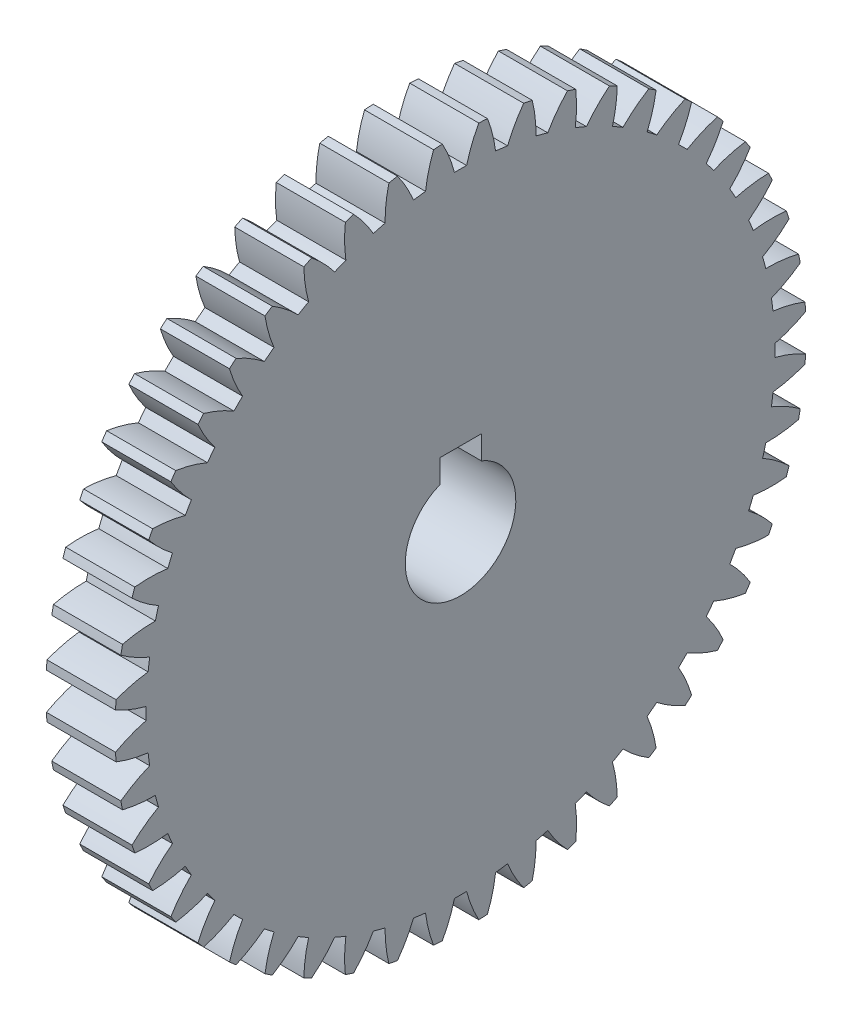
SolidWorks part; units mm, degrees
ref_plane "Plane1" through (0, 0, 0) normal (0, 0, 1) x (1, 0, 0)
ref_plane "Plane2" through (0, 0, 0) normal (0, 1, 0) x (1, 0, 0)
ref_plane "Plane3" through (0, 0, 0) normal (1, 0, 0) x (0, 0, -1)
other "Configuration Table"
sketch "HoldingSke" plane through (0, 0, 0) normal (0, 1, 0) x (1, 0, 0)
  line L0 (0, 0) -> (0.6691, -0.7431)
  line L1 (-15, 0) -> (100, 0) construction
  line L2 (0, 0) -> (-2.1039, 2.3779)
  line L3 (0, 0) -> (-11.863, 4.5341)
  line L4 (0, 0) -> (5.7786, 6.4178)
  line L5 (0, 0) -> (-9.3695, -3.4946)
  line L6 (0, 0) -> (-4.1448, -2.7965)
  line L7 (-2.1039, 2.3779) -> (0.0486, 12.1435)
  line L8 (-76.2, 54.61) -> (-74.8, 54.61)
  line L9 (-71.009, 38.7566) -> (-53.1078, 45.2721)
  line L10 (-76.2, 71.12) -> (104.1128, 71.12)
  line L11 (0, 0) -> (-5, 0)
  line L12 (-76.2, 101.6) -> (-76.162, 101.6)
  line L13 (24.9733, 27.94) -> (52.9518, 28.4284)
  line L14 (24.9733, 27.94) -> (24.9743, 27.94)
  line L15 (24.9733, 27.94) -> (100.4006, 29.5858)
  line L16 (-63.627, -1) -> (-12.827, -1)
  circle A0 centre (0, 0) radius 4
  circle A1 centre (0, 0) radius 5
  circle A2 centre (0, 0) radius 5
  circle A3 centre (0, 0) radius 4
  dimension "MHD" = 10
  dimension "Hub_dia" = 10
  dimension "Bore" = 8
  dimension "MBD" = 8
  dimension "Num_teeth" = 48
  dimension "Pitch" = 1
  dimension "Overall_len" = 10
  dimension "Show_teeth" = 48
  dimension "Thickness" = 5
  dimension "OAL" = 10.0001
  dimension "T_dim" = 1.4
  dimension "Ap" = 20
  dimension "H" = 19.05
  dimension "Pitch_radius" = 180.3128
  dimension "Width" = 5
  dimension "Backlash" = 0.038
  dimension "Addendum_fac" = 1
  dimension "Dedendum_fac" = 1.25
  dimension "Clearance_fac" = 0.25
  dimension "Dedendum_add" = 0.001
  dimension "Module" = 1
sketch "BasProSke" plane through (0, 0, 0) normal (0, 1, 0) x (1, 0, 0)
  line L0 (-10, 0) -> (60, 0) construction
  line L1 (0, 0) -> (0, 25)
  line L2 (0, 0) -> (5, 0)
  line L3 (5, 0) -> (5, 25)
  line L4 (5, 25) -> (0, 25)
  dimension "Thickness" = 5
  dimension "Diameter" = 50
revolve "Base-Revolve" add sketch "BasProSke" angle 360 about L0
sketch "TooCutSke" plane through (0, 0, 0) normal (1, 0, 0) x (0, 0, -1)
  line L1 (0, 0) -> (0, 107) construction
  line L2 (0, 0) -> (-0.8518, 23.9849) construction
  line L3 (0, 0) -> (-3.1379, 47.8757) construction
  line L4 (-0.8518, 23.9849) -> (-1.569, 23.9379) construction
  arc A0 (0.4395, 22.7448) -> (-0.4395, 22.7448) centre (0, 0) ccw
  arc A1 (1.3336, 24.9898) -> (-1.3336, 24.9898) centre (0, 0) ccw
  circle A2 centre (0, 0) radius 24 construction
  circle A3 centre (0, 0) radius 22.5526 construction
  arc A4 (-0.4395, 22.7448) -> (-1.3336, 24.9898) centre (-9.7344, 20.3436) ccw
  arc A5 (1.3336, 24.9898) -> (0.4395, 22.7448) centre (9.7344, 20.3436) ccw
  dimension "Root_dia" = 45.498
  dimension "Overcut_dia" = 50.0508
  dimension "Pitch_dia" = 48
  dimension "Base_dia" = 45.1052
  dimension "Flank_rad" = 9.6
  dimension "Half_ang" = 3.75
  dimension "Half_CT" = 0.7188
extrude "ToothCut" cut sketch "TooCutSke" along normal through all
fillet "Breaks" [suppressed] radius 0.02
fillet "RootFillets" [suppressed] radius 0.251
pattern_circular "TeethCuts" count 48 every 7.5 about axis through (-10, 0, 0) along (1, 0, 0) of "ToothCut", "RootFillets", "Breaks"
sketch "HubNeaOneSke" plane through (0, 0, 0) normal (-1, 0, 0) x (0, 0, 1)
  circle A0 centre (0, 0) radius 5
  dimension "Diameter" = 10
extrude "HubNearOne" add sketch "HubNeaOneSke" along normal blind 5.0001
sketch "HubNeaBotSke" plane through (0, 0, 0) normal (-1, 0, 0) x (0, 0, 1)
  circle A0 centre (0, 0) radius 5
  dimension "Diameter" = 10
extrude "HubNearBoth" [suppressed] add sketch "HubNeaBotSke" along normal blind 2.5
ref_plane "FarPln" through (5, 0, 0) normal (1, 0, 0) x (0, 0, -1)
sketch "HubFarSke" plane through (5, 0, 0) normal (1, 0, 0) x (0, 0, -1)
  circle A0 centre (0, 0) radius 5
  dimension "Diameter" = 10
extrude "HubFar" [suppressed] add sketch "HubFarSke" along normal blind 2.5
sketch "BorSke" plane through (0, 0, 0) normal (1, 0, 0) x (0, 0, -1)
  circle A0 centre (0, 0) radius 4
  dimension "Diameter" = 8
extrude "Bore" cut sketch "BorSke" along normal mid plane 20.0001
sketch "KeySke" plane through (0, 0, 0) normal (1, 0, 0) x (0, 0, -1)
  line L0 (-1.5, 0) -> (-1.5, 5.4)
  line L1 (-1.5, 5.4) -> (1.5, 5.4)
  line L2 (1.5, 5.4) -> (1.5, 0)
  line L3 (0, 0) -> (0, 34) construction
  line L4 (-1.5, 0) -> (1.5, 0)
  dimension "Offset" = 5.4
  dimension "Width" = 3
extrude "Keyway" cut sketch "KeySke" along normal mid plane 20.0001
pattern_circular "Keyway2" [suppressed] count 2 every 90 about axis through (-10, 0, 0) along (1, 0, 0)
equation "' \"Module@HoldingSke\" = 6.35"
equation "' \"Num_teeth@HoldingSke\" = 12"
equation "' \"Ap@HoldingSke\" =  20"
equation "' \"Ap@HoldingSke\" = 20"
equation "' \"Width@HoldingSke\" = 0.5 * 25.4"
equation "' \"Hub_dia@HoldingSke\"= 1 * 25.4"
equation "' \"Hub_dia@HoldingSke\" = 1 * 25.4"
equation "' \"Overall_len@HoldingSke\" = 1.0 * 25.4"
equation "' \"Bore@HoldingSke\" = 0.75 * 25.4"
equation "' \"T_dim@HoldingSke\" = 0.1 * 25.4"
equation "' \"Width@KeySke\" = 0.25 * 25.4"
equation "' \"Show_teeth@HoldingSke\" = 13"
equation "' \"Backlash@HoldingSke\" = 0.009 * 25.4"
equation "' \"Addendum_fac@HoldingSke\" = 1.0"
equation "' \"Dedendum_fac@HoldingSke\" = 1.25"
equation "' \"Dedendum_add@HoldingSke\" = 0.00005 * 25.4"
equation "' \"Clearance_fac@HoldingSke\" = 0.25"
equation "\"Pitch@HoldingSke\" = 1 / \"Module@HoldingSke\""
equation "\"Overcut_dia@TooCutSke\" = (\"Num_teeth@HoldingSke\" + 2 * \"Addendum_fac@HoldingSke\") / \"Pitch@HoldingSke\" + 0.002 * 25.4"
equation "\"Pitch_dia@TooCutSke\" = \"Num_teeth@HoldingSke\" / \"Pitch@HoldingSke\""
equation "\"Base_dia@TooCutSke\" = \"Num_teeth@HoldingSke\" / \"Pitch@HoldingSke\" * cos((\"Ap@HoldingSke\"  * 3.14159265 / 180))"
equation "\"Root_dia@TooCutSke\" = (\"Num_teeth@HoldingSke\" + 2) / \"Pitch@HoldingSke\" - 2 * (\"Addendum_fac@HoldingSke\" + \"Dedendum_fac@HoldingSke\") / \"Pitch@HoldingSke\" - \"Dedendum_add@HoldingSke\" * 2"
equation "\"Half_ang@TooCutSke\" = 180 / \"Num_teeth@HoldingSke\""
equation "\"Half_CT@TooCutSke\" = \"Num_teeth@HoldingSke\" / \"Pitch@HoldingSke\" * sin((3.14159265 / 2 / \"Num_teeth@HoldingSke\")) / 2 - 7 * \"Backlash@HoldingSke\" / 4"
equation "\"Flank_rad@TooCutSke\" = \"Num_teeth@HoldingSke\" / \"Pitch@HoldingSke\" / 5"
equation "\"Radius@RootFillets\" = \"Clearance_fac@HoldingSke\" / \"Pitch@HoldingSke\" + \"Dedendum_add@HoldingSke\""
equation "\"Break_rad@Breaks\" = 0.02 / \"Pitch@HoldingSke\""
equation "\"Thickness@HoldingSke\" = \"Width@HoldingSke\""
equation "\"OAL@HoldingSke\" = \"Thickness@HoldingSke\""
equation "\"MHD@HoldingSke\" = (\"Num_teeth@HoldingSke\" + 2) / \"Pitch@HoldingSke\" - 2 * (\"Addendum_fac@HoldingSke\" + \"Dedendum_fac@HoldingSke\")  / \"Pitch@HoldingSke\" - \"Dedendum_add@HoldingSke\" * 2"
equation "\"MBD@HoldingSke\" = (\"Num_teeth@HoldingSke\" + 2) / \"Pitch@HoldingSke\" - 2 * (\"Addendum_fac@HoldingSke\" + \"Dedendum_fac@HoldingSke\")  / \"Pitch@HoldingSke\" - \"Dedendum_add@HoldingSke\" * 2 - 0.002 * 25.4"
equation "\"MHD@HoldingSke\" = ((sgn( \"MHD@HoldingSke\" - \"Hub_dia@HoldingSke\" )-1)*( \"MHD@HoldingSke\" - \"Hub_dia@HoldingSke\" ))/-2+ \"Hub_dia@HoldingSke\""
equation "\"MBD@HoldingSke\" = ((sgn( \"MBD@HoldingSke\" - \"Bore@HoldingSke\" )-1)*( \"MBD@HoldingSke\" - \"Bore@HoldingSke\" ))/-2+ \"Bore@HoldingSke\""
equation "\"OAL@HoldingSke\" = ((sgn( \"OAL@HoldingSke\" - \"Overall_len@HoldingSke\" )+1)*( \"OAL@HoldingSke\" - \"Overall_len@HoldingSke\" ))/2 + \"Overall_len@HoldingSke\" + 0.000002 * 25.4"
equation "\"Num_teeth@TeethCuts\" = int( \"Show_teeth@HoldingSke\" ) + 1"
equation "\"Num_teeth@TeethCuts\" = ((sgn( \"Num_teeth@TeethCuts\" - \"Num_teeth@HoldingSke\" )-1)*( \"Num_teeth@TeethCuts\" - \"Num_teeth@HoldingSke\" ))/-2+ \"Num_teeth@HoldingSke\""
equation "\"Num_teeth@TeethCuts\" = ((sgn( \"Num_teeth@TeethCuts\" - 2.0)+1)*( \"Num_teeth@TeethCuts\" - 2.0))/2 +2.0"
equation "\"Angle@TeethCuts\" = 360.0 / \"Num_teeth@HoldingSke\""
equation "\"Diameter@BasProSke\" = (\"Num_teeth@HoldingSke\" + 2 * \"Addendum_fac@HoldingSke\") / \"Pitch@HoldingSke\""
equation "\"Thickness@BasProSke\"  = \"Thickness@HoldingSke\""
equation "' \"Fillet_rad@BasProSke\" =  \"Thickness@HoldingSke\" * 0.05"
equation "' \"Fillet_rad@BasProSke\" = \"Thickness@HoldingSke\" * 0.05"
equation "\"MHD@HoldingSke\" = ((sgn( \"MHD@HoldingSke\" - \"Root_dia@TooCutSke\" )-1)*( \"MHD@HoldingSke\" - \"Root_dia@TooCutSke\" ))/-2+ \"Root_dia@TooCutSke\""
equation "\"Diameter@HubNeaOneSke\" = \"MHD@HoldingSke\""
equation "\"Length@HubNearOne\" = \"OAL@HoldingSke\" - \"Thickness@BasProSke\""
equation "\"Diameter@HubNeaBotSke\" = \"MHD@HoldingSke\""
equation "\"Length@HubNearBoth\" = ( \"OAL@HoldingSke\" - \"Thickness@BasProSke\" ) / 2.0"
equation "\"Thickness@FarPln\" = \"Thickness@BasProSke\""
equation "\"Diameter@HubFarSke\" = \"MHD@HoldingSke\""
equation "\"Length@HubFar\" = ( \"OAL@HoldingSke\" - \"Thickness@BasProSke\" ) / 2.0"
equation "\"Diameter@BorSke\" = \"MBD@HoldingSke\""
equation "\"D1@Bore\" = \"OAL@HoldingSke\" * 2.0"
equation "\"D1@Keyway\" = \"OAL@HoldingSke\" * 2.0"
equation "\"Offset@KeySke\" = \"T_dim@HoldingSke\" + \"MBD@HoldingSke\" / 2.0"
